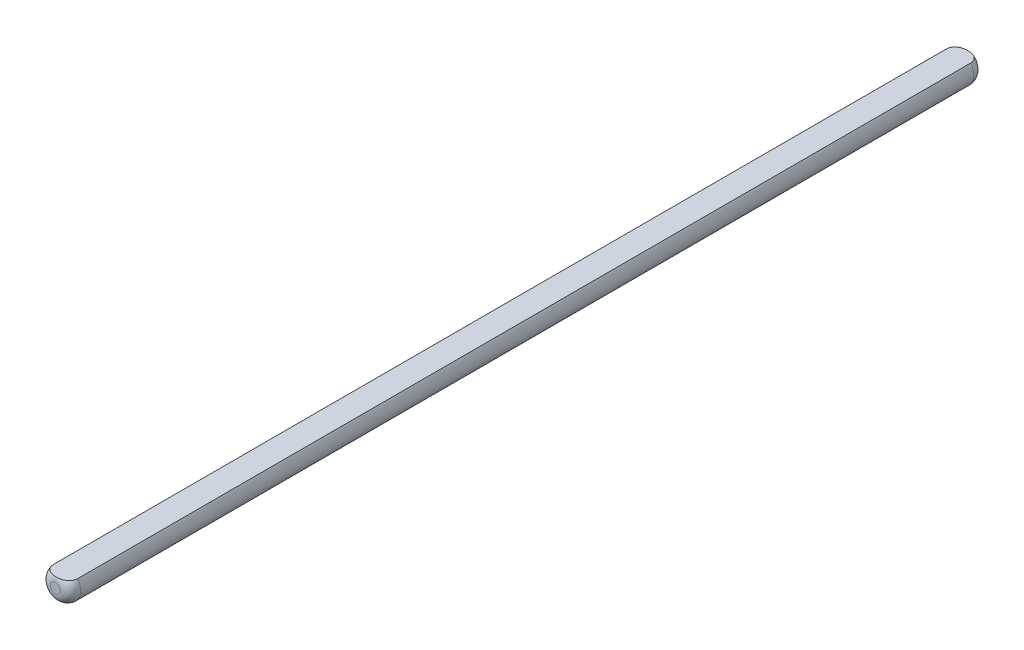
SolidWorks part; units mm, degrees
ref_plane "Plan de face" through (0, 0, 0) normal (0, 0, 1) x (1, 0, 0)
ref_plane "Plan de dessus" through (0, 0, 0) normal (0, 1, 0) x (1, 0, 0)
ref_plane "Plan de droite" through (0, 0, 0) normal (1, 0, 0) x (0, 0, -1)
sketch "Esquisse1" plane through (0, 0, 0) normal (0, 0, 1) x (1, 0, 0)
  circle A0 centre (0, 0) radius 3
  dimension "D1" = 6
extrude "Boss.-Extru.1" add sketch "Esquisse1" along normal blind 180
fillet "Congé1" radius 2 2 edges at (3, 0, 0) (3, 0, 180)
sketch "Esquisse2" plane through (0, 0, 180) normal (0, 0, 1) x (1, 0, 0)
  line L1 (-3, 3) -> (3, 3)
  line L2 (-3, 3) -> (-3, 1.8)
  line L3 (-3, 1.8) -> (3, 1.8)
  line L4 (3, 3) -> (3, 1.8)
  circle A0 centre (0, 0) radius 3 construction
  point P6 (0, 3)
  dimension "D1" = 6
  dimension "D2" = 1.2
extrude "Enlèv. mat.-Extru.1" cut sketch "Esquisse2" against normal through all
sketch "Esquisse3" plane through (0, 0, 0) normal (0, 0, -1) x (-1, 0, 0)
  point P0 (0, 0)
